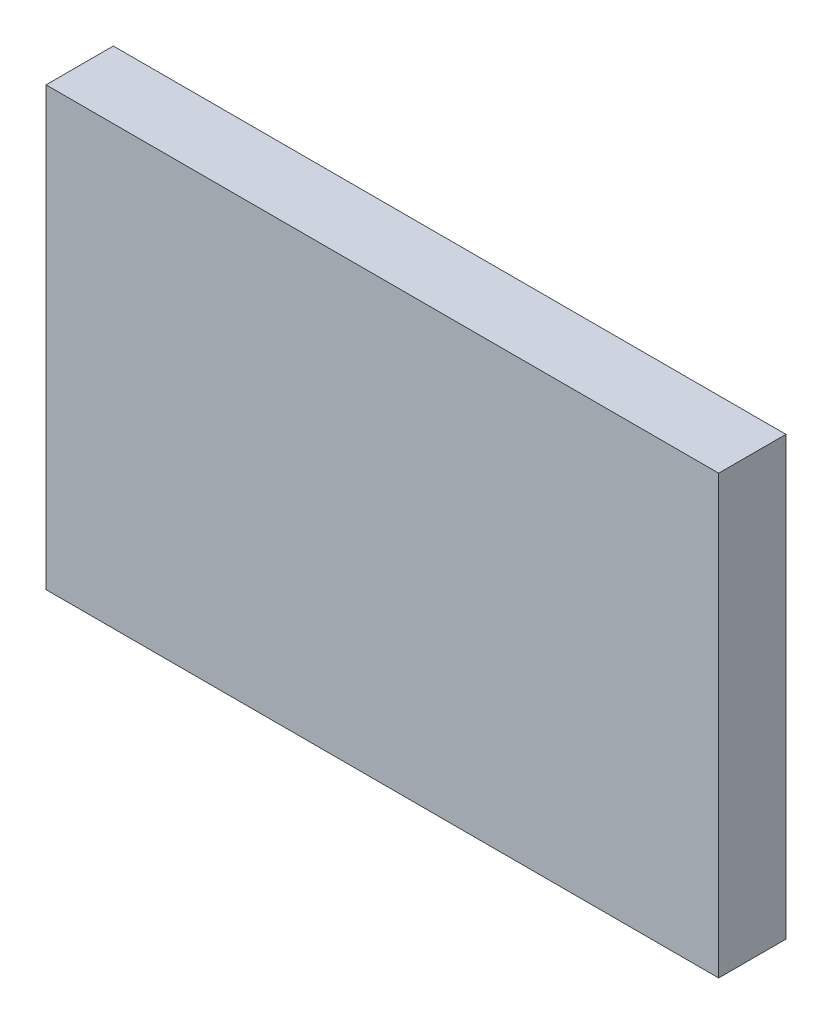
SolidWorks part; units mm, degrees
ref_plane "Front Plane" through (0, 0, 0) normal (0, 0, 1) x (1, 0, 0)
ref_plane "Top Plane" through (0, 0, 0) normal (0, 1, 0) x (1, 0, 0)
ref_plane "Right Plane" through (0, 0, 0) normal (1, 0, 0) x (0, 0, -1)
sketch "Sketch1" plane through (0, 0, 0) normal (0, 0, 1) x (1, 0, 0)
  line L1 (0, 0) -> (20, 0)
  line L2 (0, 0) -> (0, 13)
  line L3 (0, 13) -> (20, 13)
  line L4 (20, 0) -> (20, 13)
  dimension "D1" = 20
  dimension "D2" = 13
extrude "Boss-Extrude1" add sketch "Sketch1" along normal blind 9
sketch "Sketch2" plane through (0, 0, 9) normal (0, 0, 1) x (1, 0, 0)
  line L0 (0, 13) -> (0, 0) construction
  line L1 (2, 11) -> (18, 11)
  line L2 (2, 11) -> (2, 2)
  line L3 (2, 2) -> (18, 2)
  line L4 (18, 11) -> (18, 2)
  line L5 (20, 13) -> (0, 13) construction
  dimension "D1" = 16
  dimension "D2" = 9
  dimension "D3" = 2
  dimension "D4" = 2
extrude "Cut-Extrude1" cut sketch "Sketch2" against normal blind 7
sketch "Sketch3" plane through (0, 0, 0) normal (0, -1, 0) x (1, 0, 0)
  line L2 (0, 0) -> (20, 0) construction
  line L3 (0, 9) -> (0, 0) construction
  line L4 (20, 9) -> (20, 0) construction
  circle A3 centre (3.5, 3.5) radius 1.5
  circle A4 centre (10, 3.5) radius 1.5
  circle A5 centre (16.5, 3.5) radius 1.5
  point P6 (0, 0)
  dimension "D1" = 3
  dimension "D2" = 3
  dimension "D3" = 3
  dimension "D4" = 3.5
  dimension "D5" = 3.5
  dimension "D6" = 3.5
  dimension "D7" = 3.5
  dimension "D8" = 3.5
  dimension "D9" = 6.5
extrude "Cut-Extrude2" cut sketch "Sketch3" against normal blind 7
sketch "Sketch5" plane through (0, 0, 9) normal (0, 0, 1) x (1, 0, 0)
  line L1 (0, 13) -> (20, 13)
  line L2 (0, 13) -> (0, 0)
  line L3 (0, 0) -> (20, 0)
  line L4 (20, 13) -> (20, 0)
extrude "Cut-Extrude4" cut sketch "Sketch5" against normal blind 7
